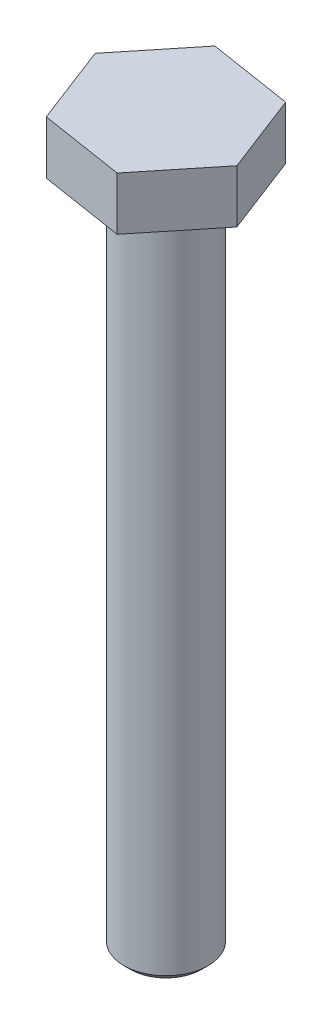
SolidWorks part; units mm, degrees
ref_plane "Front Plane" through (0, 0, 0) normal (0, 0, 1) x (1, 0, 0)
ref_plane "Top Plane" through (0, 0, 0) normal (0, 1, 0) x (1, 0, 0)
ref_plane "Right Plane" through (0, 0, 0) normal (1, 0, 0) x (0, 0, -1)
sketch "Sketch1" plane through (0, 0, 0) normal (0, 1, 0) x (1, 0, 0)
  circle A0 centre (0, 0) radius 3.175
extrude "Boss-Extrude1" add sketch "Sketch1" along normal blind 50.8
sketch "Sketch2" plane through (0, 50.8, 0) normal (0, 1, 0) x (1, 0, 0)
  line L1 (-2.3049, 5.9875) -> (-6.3378, 0.9976)
  line L2 (-6.3378, 0.9976) -> (-4.0328, -4.9899)
  line L3 (-4.0328, -4.9899) -> (2.3049, -5.9875)
  line L4 (2.3049, -5.9875) -> (6.3378, -0.9976)
  line L5 (6.3378, -0.9976) -> (4.0328, 4.9899)
  line L6 (4.0328, 4.9899) -> (-2.3049, 5.9875)
  circle A0 centre (0, 0) radius 5.5562 construction
extrude "Boss-Extrude2" add sketch "Sketch2" along normal blind 4
chamfer "Chamfer1" distance 0.5 angle 45 1 edges at (0, 0, 3.175)
